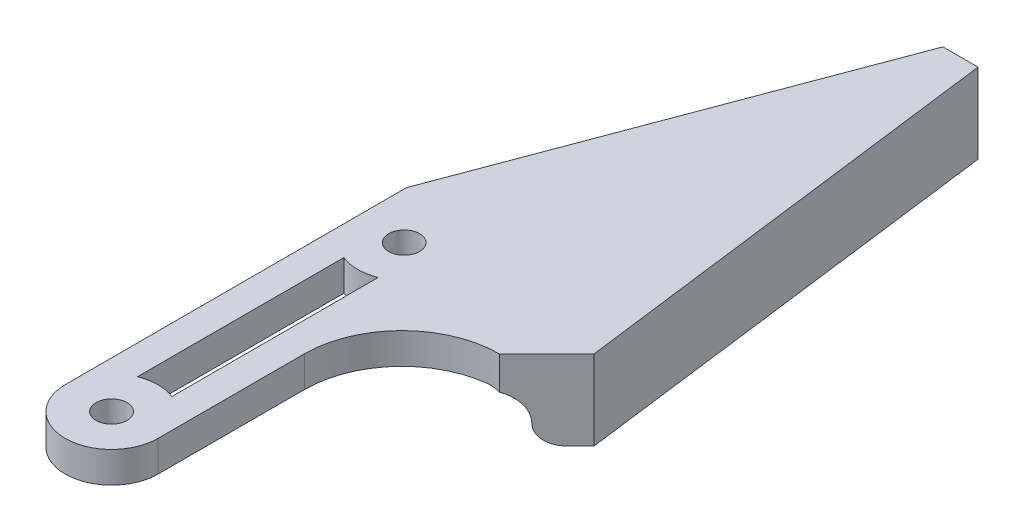
SolidWorks part; units mm, degrees
material "1060-H14"
ref_plane "Alzado" through (0, 0, 0) normal (0, 0, 1) x (1, 0, 0)
ref_plane "Planta" through (0, 0, 0) normal (0, 1, 0) x (1, 0, 0)
ref_plane "Vista lateral" through (0, 0, 0) normal (1, 0, 0) x (0, 0, -1)
sketch "Croquis1" plane through (0, 0, 0) normal (0, 1, 0) x (1, 0, 0)
  line L0 (-12.5, 40) -> (12.5, -40) construction
  line L1 (-12.5, 40) -> (12.5, 40) construction
  line L2 (-12.5, 40) -> (-12.5, -40) construction
  line L3 (-12.5, -40) -> (12.5, -40) construction
  line L4 (12.5, 40) -> (12.5, -40) construction
  line L5 (-12.5, 0) -> (-12.5, -40)
  line L6 (-12.5, -40) -> (-2.975, -40)
  line L7 (-2.975, -40) -> (-2.975, -20)
  line L8 (7.025, -10) -> (12.5, -10)
  line L9 (12.5, -10) -> (12.5, 40)
  line L10 (12.5, 40) -> (2.5, 40)
  line L11 (2.5, 40) -> (-12.5, 0)
  circle A0 centre (-7.7375, -5) radius 1.5875
  circle A1 centre (-7.7375, -35) radius 1.5875
  arc A2 (-2.975, -20) -> (7.025, -10) centre (7.025, -20) cw
  dimension "D5" = 3.175
  dimension "D6" = 3.175
  dimension "D12" = 10
  dimension "D1" = 25
  dimension "D2" = 80
  dimension "D3" = 9.525
  dimension "D4" = 30
  dimension "D7" = 4.7625
  dimension "D8" = 5
  dimension "D9" = 10
  dimension "D10" = 40
  dimension "D11" = 50
extrude "Saliente-Extruir1" add sketch "Croquis1" along normal blind 3.175
sketch "Croquis2" plane through (0, 3.175, 0) normal (0, 1, 0) x (1, 0, 0)
  line L0 (12.5, -10) -> (6.1, 40)
  line L1 (12.5, 40) -> (2.5, 40) construction
  line L2 (6.1, 40) -> (12.5, 40)
  line L3 (12.5, 40) -> (12.5, -10)
  dimension "D1" = 6.4
extrude "Cortar-Extruir1" cut sketch "Croquis2" against normal blind 3.175
sketch "Croquis3" plane through (0, 3.175, 0) normal (0, 1, 0) x (1, 0, 0)
  line L1 (-2.975, -40) -> (-2.975, -20) construction
  line L2 (-12.5, -35) -> (-12.5, -40)
  line L3 (-12.5, -40) -> (-2.975, -40)
  line L4 (-2.975, -40) -> (-2.975, -35)
  line L5 (-9.5, -9.4271) -> (-9.5, -30.5756)
  line L6 (-5.975, -14.8038) -> (-5.975, -30.5756)
  line L7 (-12.5, 0) -> (-12.5, -40) construction
  line L8 (-5.975, -14.8038) -> (-5.975, -9.4271)
  line L22 (7.025, -6) -> (7.9554, -6)
  line L23 (7.9554, -6) -> (3.2646, 30.6468)
  line L24 (3.2646, 30.6468) -> (-8.5, -0.7253)
  line L25 (-8.5, -0.7253) -> (-8.5, -36)
  line L26 (-8.5, -36) -> (-6.975, -36)
  line L27 (-6.975, -36) -> (-6.975, -20)
  line L28 (7.025, -6) -> (7.9554, -6)
  arc A2 (-9.5, -9.4271) -> (-5.975, -9.4271) centre (-7.7375, -5) ccw
  arc A3 (-12.5, -35) -> (-2.975, -35) centre (-7.7375, -35) ccw
  arc A4 (-5.975, -30.5756) -> (-9.5, -30.5756) centre (-7.7375, -35) ccw
  arc A6 (7.025, -6) -> (-6.975, -20) centre (7.025, -20) ccw
  dimension "D1" = 9.53
  dimension "D2" = 3
  dimension "D3" = 3
  dimension "D5" = 4
extrude "Cortar-Extruir3" cut sketch "Croquis3" against normal blind 10 contours A4 L6 L8 A2 L5 | A3 L4 L3 L2
sketch "Croquis4" plane through (0, 3.175, 0) normal (0, 1, 0) x (1, 0, 0)
  line L0 (6.1, 40) -> (12.5, -10) construction
  line L1 (7.025, -10) -> (11.8787, -5.1463)
  line L2 (11.8787, -5.1463) -> (12.5, -10)
  line L3 (12.5, -10) -> (7.025, -10)
  dimension "D3" = 45
extrude "Cortar-Extruir4" cut sketch "Croquis4" against normal blind 10
sketch "Esquisse1" plane through (0, 3.175, 0) normal (0, 1, 0) x (1, 0, 0)
  line L0 (11.8787, -5.1463) -> (6.1, 40)
  line L1 (6.1, 40) -> (2.5, 40)
  line L2 (2.5, 40) -> (8.6872, -8.3378)
  line L3 (8.6872, -8.3378) -> (11.8787, -5.1463)
  line L4 (11.8787, -5.1463) -> (7.025, -10) construction
extrude "Boss.-Extru.1" add sketch "Esquisse1" against normal blind 8.18
fillet "Congé1" radius 2 1 edges at (5.5936, -5.005, -15.8311)
fillet "Congé2" radius 3 1 edges at (5.5936, 0, -15.8311)
